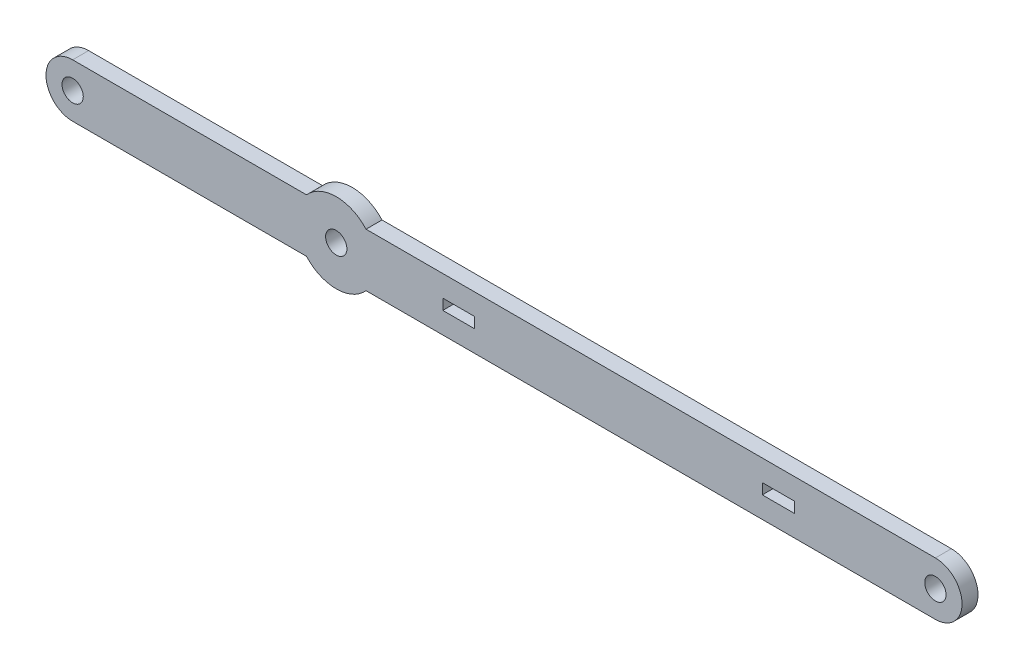
SolidWorks part; units mm, degrees
ref_plane "前视基准面" through (0, 0, 0) normal (0, 0, 1) x (1, 0, 0)
ref_plane "上视基准面" through (0, 0, 0) normal (0, 1, 0) x (1, 0, 0)
ref_plane "右视基准面" through (0, 0, 0) normal (1, 0, 0) x (0, 0, -1)
sketch "草图3" plane through (0, 0, 0) normal (0, 0, 1) x (1, 0, 0)
  line L0 (0, 0) -> (162, 0) construction
  line L1 (55, 0) -> (-55, 0) construction
  line L2 (0, 5) -> (43.9098, 5)
  line L3 (0, -5) -> (43.9098, -5)
  line L4 (55.0902, -5) -> (162, -5)
  line L5 (55.0902, 5) -> (162, 5)
  line L6 (69.5, 1) -> (69.5, -1)
  line L7 (69.5, -1) -> (75.5, -1)
  line L8 (75.5, -1) -> (75.5, 1)
  line L9 (75.5, 1) -> (69.5, 1)
  line L10 (129.5, 1) -> (129.5, -1)
  line L11 (129.5, -1) -> (135.5, -1)
  line L12 (135.5, -1) -> (135.5, 1)
  line L13 (135.5, 1) -> (129.5, 1)
  arc A0 (0, 5) -> (0, -5) centre (0, 0) ccw
  arc A1 (162, -5) -> (162, 5) centre (162, 0) ccw
  arc A2 (43.9098, -5) -> (55.0902, -5) centre (49.5, 0) ccw
  circle A3 centre (162, 0) radius 2
  circle A4 centre (0, 0) radius 2
  circle A5 centre (49.5, 0) radius 2
  arc A6 (55.0902, 5) -> (43.9098, 5) centre (49.5, 0) ccw
  point P5 (81, 0)
extrude "凸台-拉伸1" add sketch "草图3" along normal mid plane 3
